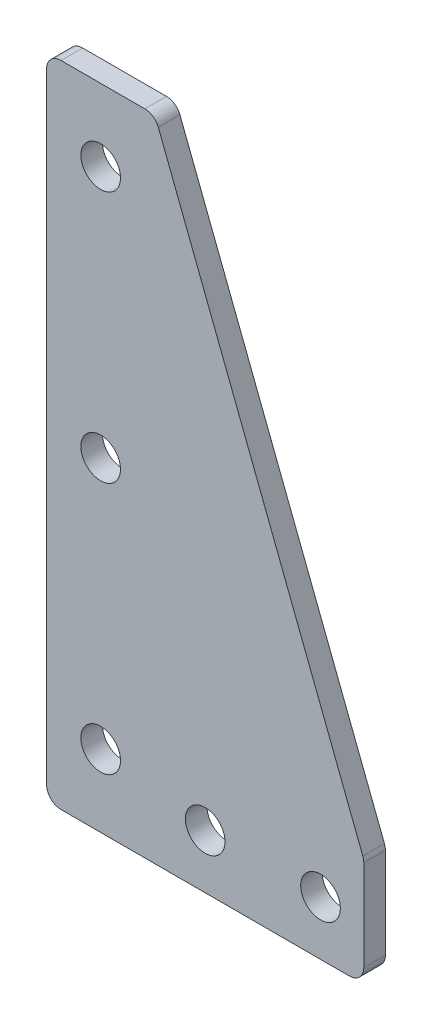
SolidWorks part; units mm, degrees
other "Objet de détail1"
ref_plane "Front" through (0, 0, 0) normal (0, 0, 1) x (1, 0, 0)
ref_plane "Top" through (0, 0, 0) normal (0, 1, 0) x (1, 0, 0)
ref_plane "Right" through (0, 0, 0) normal (1, 0, 0) x (0, 0, -1)
sketch "Esquisse1" plane through (0, 0, 0) normal (0, 0, 1) x (1, 0, 0)
  line L0 (0, 0) -> (44, 0)
  line L1 (44, 0) -> (44, 15)
  line L2 (44, 15) -> (15, 90)
  line L3 (15, 90) -> (0, 90)
  line L4 (0, 90) -> (0, 0)
  dimension "D1" = 44
  dimension "D2" = 15
  dimension "D3" = 15
  dimension "D4" = 90
extrude "Boss.-Extru.1" add sketch "Esquisse1" along normal blind 3
sketch "Esquisse2" plane through (0, 0, 3) normal (0, 0, 1) x (1, 0, 0)
  line L0 (7.5, 0) -> (7.5, 90) construction
  line L1 (0, 0) -> (44, 0) construction
  line L2 (15, 90) -> (0, 90) construction
  line L3 (44, 7.5) -> (0, 7.5) construction
  line L4 (44, 0) -> (44, 15) construction
  line L5 (0, 90) -> (0, 0) construction
  line L6 (22, 7.5) -> (22, 17.4042) construction
  line L7 (0, 45) -> (7.5, 45) construction
  circle A0 centre (7.5, 10) radius 2.75
  circle A1 centre (7.5, 45) radius 2.75
  circle A2 centre (7.5, 80) radius 2.75
  circle A4 centre (22, 7.5) radius 2.75
  circle A5 centre (38, 7.5) radius 2.75
  dimension "D1" = 5.5
  dimension "D2" = 35
  dimension "D3" = 16
  dimension "D6" = 6
extrude "Enlèv. mat.-Extru.1" cut sketch "Esquisse2" against normal through all both and the other way through all
fillet "Congé1" radius 2 5 edges at (44, 0, 1.5) (0, 0, 1.5) (15, 90, 1.5) (0, 90, 1.5) (44, 15, 1.5)
sketch "Esquisse3" [suppressed] plane through (0, 0, 3) normal (0, 0, 1) x (1, 0, 0)
  line L0 (38, 7.5) -> (22, 7.5) construction
  circle A0 centre (22, 7.5) radius 2.75
  circle A1 centre (38, 7.5) radius 2.75 construction
  dimension "D1" = 16
extrude "Enlèv. mat.-Extru.2" [suppressed] cut sketch "Esquisse3" against normal through all both and the other way through all
